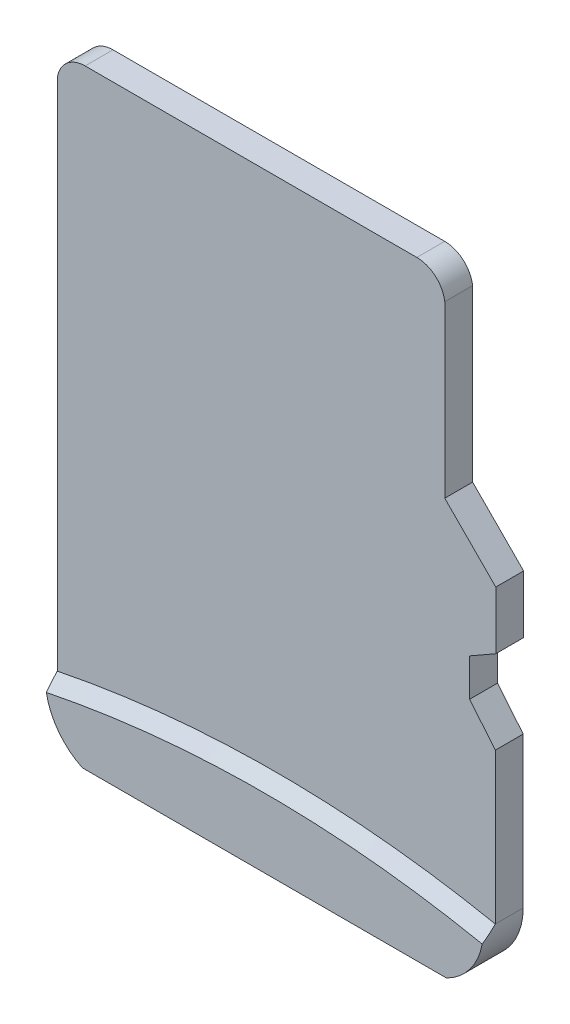
SolidWorks part; units mm, degrees
ref_plane "Front Plane" through (0, 0, 0) normal (0, 0, 1) x (1, 0, 0)
ref_plane "Top Plane" through (0, 0, 0) normal (0, 1, 0) x (1, 0, 0)
ref_plane "Right Plane" through (0, 0, 0) normal (1, 0, 0) x (0, 0, -1)
sketch "Sketch1" plane through (0, 0, 0) normal (0, 0, 1) x (1, 0, 0)
  line L0 (19.1531, 24.0335) -> (27.4834, 24.0335)
  line L1 (28.1851, 23.4204) -> (28.1851, 19.1475)
  line L2 (28.1851, 19.1475) -> (29.466, 17.856)
  line L3 (29.466, 17.856) -> (29.466, 16.4054)
  line L4 (28.8097, 16.0308) -> (28.8097, 15.0873)
  line L5 (28.8097, 15.0873) -> (29.4551, 14.3035)
  line L6 (29.4551, 14.3035) -> (29.4551, 10.5216)
  line L7 (28.8097, 16.0308) -> (29.466, 16.4054)
  line L8 (18.4539, 23.4204) -> (18.4539, 10.5216)
  line L9 (19.3821, 9.0335) -> (28.5269, 9.0335)
  arc A0 (28.1851, 23.4204) -> (27.4834, 24.0335) centre (27.486, 23.3283) ccw
  arc A1 (18.4539, 10.5216) -> (19.3821, 9.0335) centre (20.0948, 10.5115) ccw
  arc A2 (29.4551, 10.5216) -> (18.4539, 10.5216) centre (23.9545, -16.6696) ccw
  arc A3 (28.5269, 9.0335) -> (29.4551, 10.5216) centre (27.7888, 10.5274) ccw
  arc A4 (19.1556, 24.0335) -> (18.4539, 23.4204) centre (19.1531, 23.3283) ccw
sketch "Sketch2" plane through (0, 0, 0) normal (0, 0, 1) x (1, 0, 0)
  line L0 (19.3821, 9.0335) -> (28.5269, 9.0335)
  arc A0 (18.4539, 10.5216) -> (29.4551, 10.5216) centre (23.9545, -16.6696) cw
  arc A1 (29.4551, 10.5216) -> (28.5269, 9.0335) centre (27.7888, 10.5274) cw
  arc A2 (19.3821, 9.0335) -> (18.4539, 10.5216) centre (20.0948, 10.5115) cw
extrude "Extrude1" add sketch "Sketch1" along normal blind 0.7 contours L0 A4 L8 A2 L6 L5 L4 L7 L3 L2 L1 A0 | L9 A3 A2 A1
extrude "Extrude2" add sketch "Sketch2" along normal blind 1
draft "Draft1" type of draft neutral plane draft angle 45 faces to draft 1 face at (23.9545, 10.797, 0.85) neutral plane through (23.9599, 1.9183, 0.7) neutral plane normal (0, 0, 1) parameters "D1"=45
